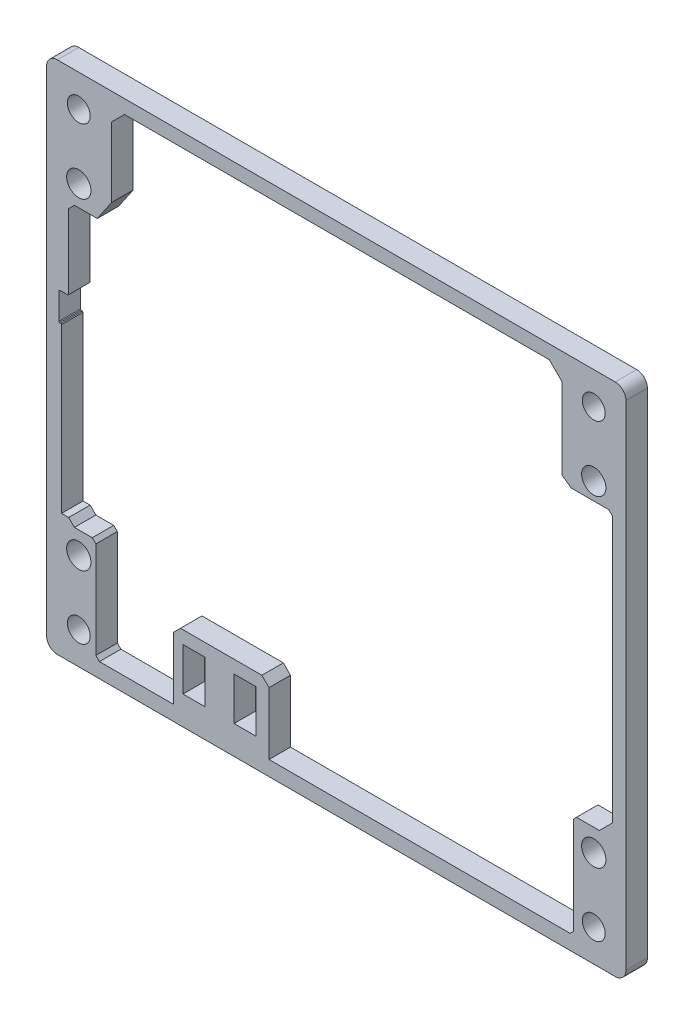
SolidWorks part; units mm, degrees
ref_plane "Alzado" through (0, 0, 0) normal (0, 0, 1) x (1, 0, 0)
ref_plane "Planta" through (0, 0, 0) normal (0, 1, 0) x (1, 0, 0)
ref_plane "Vista lateral" through (0, 0, 0) normal (1, 0, 0) x (0, 0, -1)
sketch "Model" plane through (0, 0, 0) normal (0, 0, 1) x (1, 0, 0)
  line L0 (79.3268, -113.0674) -> (79.3268, -107.0674)
  line L1 (89.5722, -107.0674) -> (89.5722, -113.0674)
  line L2 (86.4722, -113.0674) -> (86.4722, -107.0674)
  line L3 (89.5722, -113.0674) -> (86.4722, -113.0674)
  line L4 (86.4722, -107.0674) -> (89.5722, -107.0674)
  line L5 (82.4268, -113.0674) -> (79.3268, -113.0674)
  line L6 (82.4268, -107.0674) -> (82.4268, -113.0674)
  line L7 (79.3268, -107.0674) -> (82.4268, -107.0674)
  line L8 (63.3513, -62.2754) -> (63.3513, -72.6894)
  line L9 (138.8664, -60.9754) -> (139.3664, -61.4754)
  line L10 (133.9682, -114.4778) -> (133.4682, -114.9778)
  line L11 (66.6513, -100.4778) -> (67.1513, -100.9778)
  line L12 (67.6513, -114.9778) -> (67.1513, -114.4778)
  line L13 (139.3664, -61.4754) -> (139.3664, -98.6674)
  line L14 (90.3616, -105.2775) -> (91.3616, -106.2775)
  line L15 (78.9805, -105.2779) -> (77.9805, -106.2779)
  line L16 (67.6513, -114.9778) -> (77.9805, -114.9778)
  line L17 (77.9805, -106.2779) -> (77.9805, -114.9778)
  line L18 (90.3616, -105.2775) -> (78.9805, -105.2779)
  line L19 (67.3513, -61.4754) -> (69.3513, -58.5384)
  line L20 (133.6347, -60.9754) -> (138.8664, -60.9754)
  line L21 (66.6513, -100.4778) -> (64.1513, -100.4778)
  line L22 (69.3513, -58.5384) -> (69.3513, -48.7754)
  line L23 (132.356, -48.7754) -> (132.356, -60.089)
  line L24 (64.1513, -61.4754) -> (67.3513, -61.4754)
  line L25 (64.1513, -100.4778) -> (63.3513, -99.6778)
  line L26 (67.1513, -114.4778) -> (67.1513, -100.9778)
  line L27 (137.556, -100.4778) -> (139.3664, -98.6674)
  line L28 (91.3616, -114.9778) -> (133.4682, -114.9778)
  line L29 (64.1513, -61.4754) -> (63.3513, -62.2754)
  line L30 (134.356, -100.4778) -> (133.9682, -100.8625)
  line L31 (133.6347, -60.9754) -> (132.356, -60.089)
  line L32 (71.1513, -46.9754) -> (69.3513, -48.7754)
  line L33 (130.556, -46.9754) -> (132.356, -48.7754)
  line L34 (137.556, -100.4778) -> (134.356, -100.4778)
  line L35 (133.9682, -100.8625) -> (133.9682, -114.4778)
  line L36 (71.1513, -46.9754) -> (130.556, -46.9754)
  line L37 (91.3616, -106.2775) -> (91.3616, -114.9778)
  line L38 (62.2513, -76.7242) -> (62.3513, -76.8242)
  line L39 (62.0884, -76.7242) -> (61.9884, -76.6242)
  line L40 (61.9884, -72.8894) -> (62.0884, -72.7894)
  line L41 (62.0884, -76.7242) -> (62.2513, -76.7242)
  line L42 (61.9884, -72.8894) -> (61.9884, -76.6242)
  line L43 (62.3513, -99.6778) -> (63.3513, -99.6778)
  line L44 (63.2513, -72.7894) -> (62.0884, -72.7894)
  line L45 (62.3513, -76.8242) -> (62.3513, -99.6778)
  line L46 (139.7682, -45.0549) -> (61.7635, -45.0549)
  line L47 (60.2635, -46.5549) -> (60.2635, -115.5573)
  line L48 (141.2682, -115.5573) -> (141.2682, -46.5549)
  line L49 (61.7635, -117.0573) -> (139.7682, -117.0573)
  line L50 (63.2513, -72.7894) -> (63.3513, -72.6894)
  circle A0 centre (136.7685, -103.558) radius 1.7
  circle A1 centre (136.7685, -58.5546) radius 1.7
  circle A2 centre (136.7685, -112.5577) radius 1.6003
  circle A3 centre (136.7685, -49.5549) radius 1.6003
  circle A4 centre (64.7635, -103.558) radius 1.7
  circle A5 centre (64.7635, -58.5546) radius 1.7
  circle A6 centre (64.7635, -49.5549) radius 1.6003
  circle A7 centre (64.7635, -112.5577) radius 1.6003
  arc A8 (61.7635, -45.0549) -> (60.2635, -46.5549) centre (61.7635, -46.5549) ccw
  arc A9 (141.2682, -46.5549) -> (139.7682, -45.0549) centre (139.7682, -46.5549) ccw
  arc A10 (139.7682, -117.0573) -> (141.2682, -115.5573) centre (139.7682, -115.5573) ccw
  arc A11 (60.2635, -115.5573) -> (61.7635, -117.0573) centre (61.7635, -115.5573) ccw
extrude "Saliente-Extruir1" add sketch "Model" along normal blind 3
